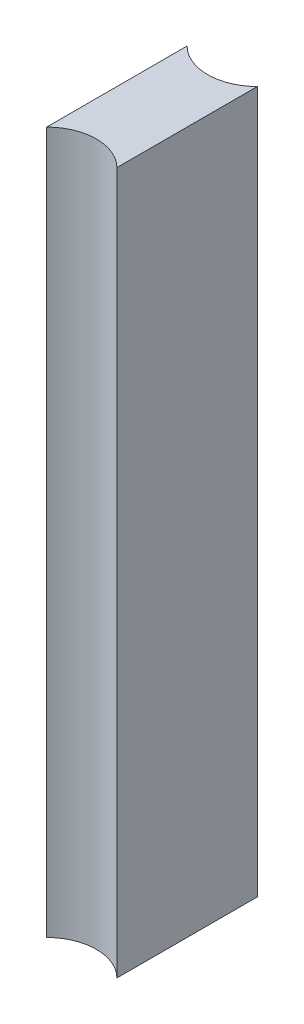
SolidWorks part; units mm, degrees
ref_plane "Front Plane" through (0, 0, 0) normal (0, 0, 1) x (1, 0, 0)
ref_plane "Top Plane" through (0, 0, 0) normal (0, 1, 0) x (1, 0, 0)
ref_plane "Right Plane" through (0, 0, 0) normal (1, 0, 0) x (0, 0, -1)
sketch "Sketch1" plane through (0, 0, 0) normal (0, 1, 0) x (1, 0, 0)
  line L0 (0, 0) -> (-0.075, 0.15) construction
  line L1 (-0.075, 0.15) -> (-0.075, -0.15)
  line L2 (-0.075, -0.15) -> (0, 0) construction
  line L3 (0, 0) -> (0.075, 0.15) construction
  line L4 (0.075, 0.15) -> (0.075, -0.15)
  line L5 (0.075, -0.15) -> (0, 0) construction
  circle A0 centre (0, 0) radius 0.075 construction
  arc A1 (0.075, 0.15) -> (-0.075, 0.15) centre (0, 0.225) cw
  arc A2 (0.075, -0.15) -> (-0.075, -0.15) centre (0, -0.225) ccw
  point P12 (0.075, 0)
  point P13 (-0.075, 0)
  dimension "D3" = 0.15
  dimension "D1" = 0.3
  dimension "D2" = 0.3
  dimension "D4" = 90
  dimension "D5" = 90
extrude "Boss-Extrude1" add sketch "Sketch1" along normal blind 1.5 contours A0 L0 L1 | L0 A0 L2 | A0 L1 L2 | L3 A0 L0 | L2 A0 L5 | A0 L4 L3 | L5 A0 L3 | A0 L5 L4
equation "\"t\"= 0.3'thickness of the sheets"
equation "\"FlexJoint\"= 0.15'Width of flextures"
equation "\"FoldJoint\"= 0.4'Width of folding joints"
equation "\"AssembleAngle\"= 90'Angle of assembly parts"
equation "\"D1@Sketch1\"=\"t\""
equation "\"D2@Sketch1\"=\"t\""
equation "\"D3@Sketch1\"=\"FlexJoint\""
